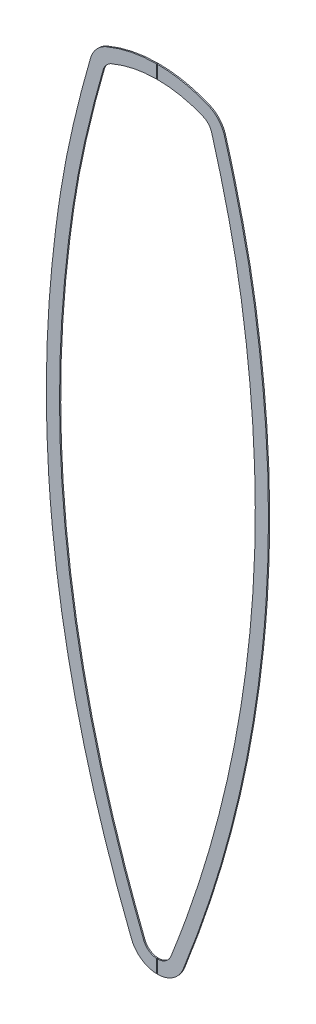
SolidWorks part; units mm, degrees
ref_plane "Front Plane" through (0, 0, 0) normal (0, 0, 1) x (1, 0, 0)
ref_plane "Top Plane" through (0, 0, 0) normal (0, 1, 0) x (1, 0, 0)
ref_plane "Right Plane" through (0, 0, 0) normal (1, 0, 0) x (0, 0, -1)
sketch "Sketch1" plane through (0, 0, 0) normal (0, 0, 1) x (1, 0, 0)
  arc A3 (-49.0125, -1227.9685) -> (50.705, -1227.9685) centre (0.8463, -1208.4369) ccw
  arc A4 (129.4409, 198.8879) -> (98.8776, 233.0674) centre (78.0841, 183.7193) ccw
  arc A5 (98.8776, 233.0674) -> (-97.1851, 233.0674) centre (0.8463, 0.4152) ccw
  arc A6 (-97.1851, 233.0674) -> (-127.7483, 198.8879) centre (-76.3916, 183.7193) ccw
  arc A10 (-25.3624, -1218.7038) -> (27.0549, -1218.7038) centre (0.8463, -1208.4369) ccw
  arc A11 (105.0812, 191.6931) -> (89.0148, 209.6604) centre (78.0841, 183.7193) ccw
  arc A12 (89.0148, 209.6604) -> (-87.3223, 209.6604) centre (0.8463, 0.4152) ccw
  arc A13 (-87.3223, 209.6604) -> (-103.3886, 191.6931) centre (-76.3916, 183.7193) ccw
  spline S0 degree 3 poles (209.7694, -536.6187) (211.0228, -517.7747) (213.0152, -480.0452) (214.9792, -404.5514) (213.888, -328.9572) (209.7594, -253.5478) (205.1823, -197.0209) (200.6097, -153.7214) (197.6515, -129.2731) (196.9436, -123.5947) knots 0.540232 0.540232 0.540232 0.540232 0.602347 0.664463 0.788693 0.850808 0.912923 0.975038 0.993843 0.993843 0.993843 0.993843
  spline S5 degree 3 poles (-195.2511, -123.5947) (-195.959, -129.2731) (-198.9172, -153.7214) (-203.4898, -197.0209) (-208.0668, -253.5478) (-212.1954, -328.9572) (-213.2867, -404.5514) (-211.3226, -480.0452) (-209.3302, -517.7747) (-208.0769, -536.6187) knots 0.540232 0.540232 0.540232 0.540232 0.559037 0.621152 0.683267 0.745382 0.869612 0.931728 0.993843 0.993843 0.993843 0.993843
  spline S6 degree 3 poles (-208.0769, -536.6187) (-207.0762, -551.6646) (-204.7559, -581.7488) (-198.8604, -641.7051) (-189.1449, -716.3383) (-176.3706, -790.5727) (-164.3492, -849.6782) (-151.1652, -908.4624) (-132.503, -981.4382) (-111.0672, -1053.564) (-92.3013, -1110.6985) (-77.4164, -1153.2755) (-65.6453, -1184.946) (-57.5547, -1206.0007) (-53.5182, -1216.4158) (-50.6708, -1223.733) (-49.184, -1227.5306) (-49.0125, -1227.9685) knots 0 0 0 0 0.062483 0.124965 0.24993 0.374895 0.437378 0.499861 0.624826 0.749791 0.812273 0.874756 0.937238 0.952859 0.96848 0.983464 0.985417 0.985417 0.985417 0.985417
  spline S7 degree 3 poles (50.705, -1227.9685) (50.8765, -1227.5306) (52.3633, -1223.733) (55.2107, -1216.4158) (59.2473, -1206.0007) (67.3379, -1184.946) (79.1089, -1153.2755) (93.9938, -1110.6985) (112.7597, -1053.564) (134.1956, -981.4382) (152.8578, -908.4624) (166.0417, -849.6782) (178.0631, -790.5727) (190.8374, -716.3383) (200.5529, -641.7051) (206.4485, -581.7488) (208.7687, -551.6646) (209.7694, -536.6187) knots 0 0 0 0 0.001953 0.016937 0.032558 0.048179 0.110661 0.173144 0.235626 0.360591 0.485556 0.548039 0.610522 0.735487 0.860452 0.922934 0.985417 0.985417 0.985417 0.985417
  spline S8 degree 3 poles (196.9436, -123.5947) (195.3132, -110.516) (191.0801, -78.7182) (183.2839, -28.3763) (174.5091, 17.8399) (166.5309, 54.6677) (160.12, 82.2522) (153.388, 109.8673) (146.4338, 137.437) (139.2187, 164.8146) (133.7731, 184.0997) (130.4533, 195.4531) (129.7753, 197.7556) (129.4409, 198.8879) knots 0.178449 0.178449 0.178449 0.178449 0.22176 0.283875 0.34599 0.377048 0.408105 0.439163 0.47022 0.501278 0.532336 0.53635 0.540232 0.540232 0.540232 0.540232
  spline S9 degree 3 poles (-127.7483, 198.8879) (-128.0828, 197.7556) (-128.7608, 195.4531) (-132.0805, 184.0997) (-137.5261, 164.8146) (-144.7413, 137.437) (-151.6954, 109.8673) (-158.4274, 82.2522) (-164.8384, 54.6677) (-172.8166, 17.8399) (-181.5914, -28.3763) (-189.3876, -78.7182) (-193.6206, -110.516) (-195.2511, -123.5947) knots 0.178449 0.178449 0.178449 0.178449 0.182331 0.186346 0.217403 0.248461 0.279518 0.310576 0.341633 0.372691 0.434806 0.496921 0.540232 0.540232 0.540232 0.540232
  spline S12 degree 1 poles (-170.0462, -126.7369) (-182.7329, -534.933) knots 0 0 1 1 construction
  spline S13 degree 1 poles (-182.7329, -534.933) (-25.3624, -1218.7038) knots 0 0 1 1 construction
  spline S14 degree 1 poles (27.0549, -1218.7038) (184.4254, -534.933) knots 0 0 1 1 construction
  spline S15 degree 1 poles (184.4254, -534.933) (171.7387, -126.7369) knots 0 0 1 1 construction
  spline S16 degree 1 poles (171.7387, -126.7369) (105.0812, 191.6931) knots 0 0 1 1 construction
  spline S17 degree 1 poles (-103.3886, 191.6931) (-170.0462, -126.7369) knots 0 0 1 1 construction
  spline S18 degree 3 poles (-170.0462, -126.7369) (-174.2693, -160.6124) (-181.2959, -228.6102) (-187.0864, -330.6334) (-187.832, -432.8729) (-184.993, -500.9516) (-182.7329, -534.933) knots 0.540232 0.540232 0.540232 0.540232 0.653635 0.767038 0.88044 0.993843 0.993843 0.993843 0.993843
  spline S19 degree 3 poles (-182.7329, -534.933) (-181.7582, -549.5883) (-179.5026, -578.8913) (-173.7864, -637.2954) (-164.3866, -710.0109) (-152.0454, -782.3598) (-140.4369, -839.9857) (-127.7089, -897.3117) (-109.696, -968.4957) (-89.0032, -1038.8974) (-70.8911, -1094.6766) (-58.9227, -1129.323) (-48.9622, -1156.8649) (-41.2927, -1177.4707) (-34.7462, -1194.5708) (-29.379, -1208.4103) (-26.7077, -1215.2697) (-25.3624, -1218.7038) knots 0 0 0 0 0.061589 0.123177 0.246354 0.369531 0.43112 0.492708 0.615886 0.739063 0.800651 0.86224 0.893034 0.923828 0.954623 0.97002 0.985417 0.985417 0.985417 0.985417
  spline S20 degree 3 poles (27.0549, -1218.7038) (28.4002, -1215.2697) (31.0715, -1208.4103) (36.4387, -1194.5708) (42.9852, -1177.4707) (50.6547, -1156.8649) (60.6153, -1129.323) (72.5836, -1094.6766) (90.6957, -1038.8974) (111.3885, -968.4957) (129.4014, -897.3117) (142.1294, -839.9857) (153.738, -782.3598) (166.0791, -710.0109) (175.4789, -637.2954) (181.1951, -578.8913) (183.4507, -549.5883) (184.4254, -534.933) knots 0 0 0 0 0.015397 0.030794 0.061589 0.092383 0.123177 0.184766 0.246354 0.369531 0.492708 0.554297 0.615886 0.739063 0.86224 0.923828 0.985417 0.985417 0.985417 0.985417
  spline S21 degree 3 poles (184.4254, -534.933) (186.6856, -500.9516) (189.5245, -432.8729) (188.7789, -330.6334) (182.9885, -228.6102) (175.9618, -160.6124) (171.7387, -126.7369) knots 0.540232 0.540232 0.540232 0.540232 0.653635 0.767038 0.88044 0.993843 0.993843 0.993843 0.993843
  spline S22 degree 3 poles (171.7387, -126.7369) (170.0554, -113.2339) (166.4511, -86.2354) (160.3229, -45.9704) (153.2883, -6.0808) (145.2572, 33.5785) (137.7304, 66.6052) (131.3253, 93.1682) (126.3802, 113.1222) (121.3227, 132.999) (116.1432, 152.6987) (111.6586, 168.9543) (107.9448, 181.9377) (106.0405, 188.4452) (105.0812, 191.6931) knots 0.178449 0.178449 0.178449 0.178449 0.223672 0.268895 0.314118 0.359341 0.404564 0.427175 0.449786 0.472398 0.495009 0.517621 0.528927 0.540232 0.540232 0.540232 0.540232
  spline S23 degree 3 poles (-103.3886, 191.6931) (-104.3479, 188.4452) (-106.2523, 181.9377) (-109.966, 168.9543) (-114.4506, 152.6987) (-119.6302, 132.999) (-124.6877, 113.1222) (-129.6327, 93.1682) (-136.0379, 66.6052) (-143.5646, 33.5785) (-151.5958, -6.0808) (-158.6304, -45.9704) (-164.7585, -86.2354) (-168.3629, -113.2339) (-170.0462, -126.7369) knots 0.178449 0.178449 0.178449 0.178449 0.189755 0.20106 0.223672 0.246283 0.268895 0.291506 0.314118 0.359341 0.404564 0.449786 0.495009 0.540232 0.540232 0.540232 0.540232
extrude "Boss-Extrude1" add sketch "Sketch1" along normal blind 2.3048
sketch "Sketch2" plane through (0, 0, 2.3048) normal (0, 0, 1) x (1, 0, 0)
  line L1 (-0.635, -1261.9848) -> (0.635, -1261.9848)
  line L2 (-0.635, -1261.9848) -> (-0.635, 252.8774)
  line L3 (-0.635, 252.8774) -> (0.635, 252.8774)
  line L4 (0.635, -1261.9848) -> (0.635, 252.8774)
  line L5 (-0.635, -1261.9848) -> (0.635, 252.8774) construction
  line L6 (-0.635, 252.8774) -> (0.635, -1261.9848) construction
  arc A0 (98.8776, 233.0674) -> (-97.1851, 233.0674) centre (0.8463, 0.4152) ccw construction
  arc A1 (-49.0125, -1227.9685) -> (50.705, -1227.9685) centre (0.8463, -1208.4369) ccw construction
  point P0 (0, -504.5537)
  point P11 (0.8463, -1261.9848)
  dimension "D1" = 1.27
extrude "Cut-Extrude1" cut sketch "Sketch2" against normal through all
